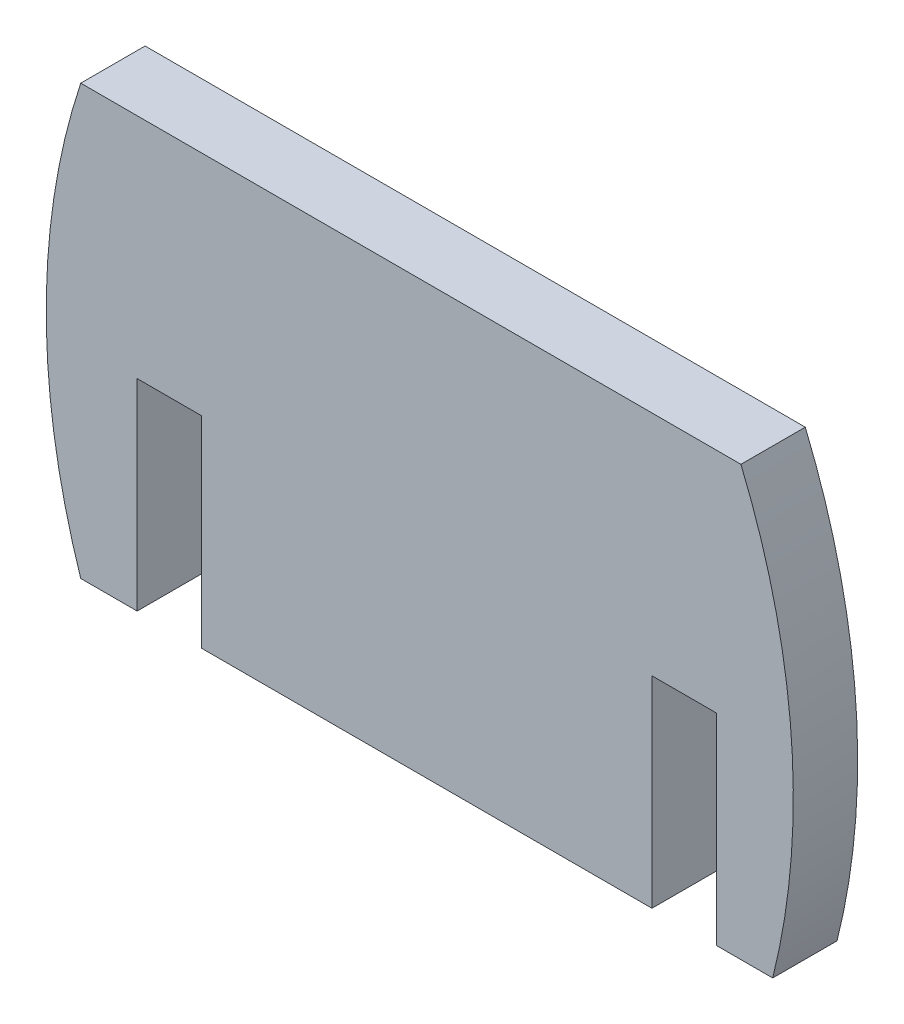
SolidWorks part; units mm, degrees
ref_plane "Front" through (0, 0, 0) normal (0, 0, 1) x (1, 0, 0)
ref_plane "Top" through (0, 0, 0) normal (0, 1, 0) x (1, 0, 0)
ref_plane "Right" through (0, 0, 0) normal (1, 0, 0) x (0, 0, -1)
sketch "Sketch1" plane through (0, 0, 0) normal (0, 0, 1) x (1, 0, 0)
  line L0 (905.9654, -110.4147) -> (908.595, -110.4147)
  line L1 (876.3358, -90.4147) -> (907.114, -90.4147)
  line L2 (881.9654, -110.4147) -> (881.9654, -101.0274)
  line L3 (878.9654, -101.0274) -> (878.9654, -110.4147)
  line L4 (905.9654, -101.0274) -> (905.9654, -110.4147)
  line L5 (902.9654, -110.4147) -> (902.9654, -101.0274)
  line L6 (892.4654, -110.4147) -> (881.9654, -110.4147)
  line L7 (878.9654, -110.4147) -> (876.3358, -110.4147)
  line L8 (892.4654, -110.4147) -> (902.9654, -110.4147)
  line L9 (881.9654, -101.0274) -> (878.9654, -101.0274)
  line L10 (902.9654, -101.0274) -> (905.9654, -101.0274)
  arc A0 (876.3358, -90.4147) -> (876.3358, -110.4147) centre (906.6014, -100.4147) ccw
  arc A1 (908.595, -110.4147) -> (907.114, -90.4147) centre (877.6805, -102.649) ccw
  dimension "D1" = 3
  dimension "D2" = 3
  dimension "D3" = 20
  dimension "D4" = 10.5
extrude "Base-Extrude" add sketch "Sketch1" along normal blind 3
